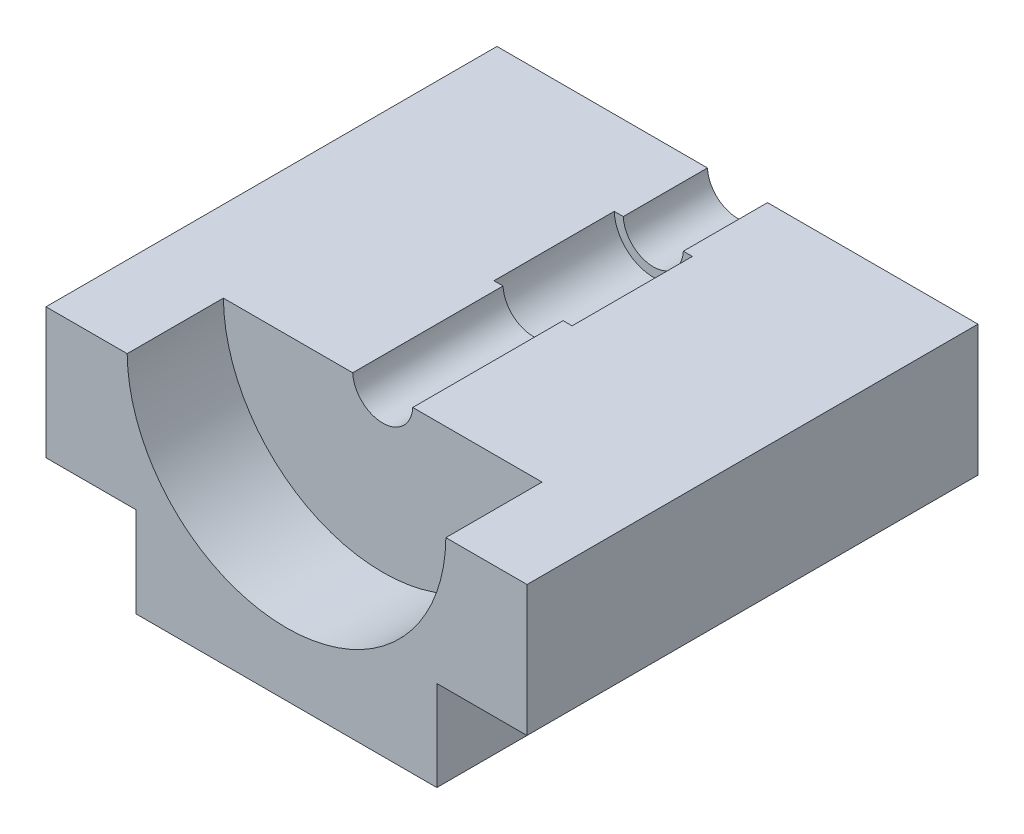
SolidWorks part; units mm, degrees
ref_plane "Front Plane" through (0, 0, 0) normal (0, 0, 1) x (1, 0, 0)
ref_plane "Top Plane" through (0, 0, 0) normal (0, 1, 0) x (1, 0, 0)
ref_plane "Right Plane" through (0, 0, 0) normal (1, 0, 0) x (0, 0, -1)
sketch "Sketch2" plane through (0, 0, 0) normal (0, 0, 1) x (1, 0, 0)
  line L5 (-35, 60) -> (-35, 50)
  line L6 (-52.5, -67.5) -> (52.5, -67.5)
  line L24 (-60, -60) -> (-60, 35)
  line L25 (-27.5, 67.5) -> (27.5, 67.5)
  line L26 (60, -60) -> (60, 35)
  line L27 (0, -100) -> (0, 100) construction
  line L28 (-100, 0) -> (100, 0) construction
  line L29 (-42.5, 42.5) -> (-52.5, 42.5)
  line L34 (35, 60) -> (35, 50)
  line L35 (42.5, 42.5) -> (52.5, 42.5)
  arc A12 (-60, 35) -> (-52.5, 42.5) centre (-52.5, 35) cw
  arc A19 (60, 35) -> (52.5, 42.5) centre (52.5, 35) ccw
  arc A20 (42.5, 42.5) -> (35, 50) centre (42.5, 50) cw
  arc A21 (35, 60) -> (27.5, 67.5) centre (27.5, 60) ccw
  arc A22 (-27.5, 67.5) -> (-35, 60) centre (-27.5, 60) ccw
  arc A23 (-42.5, 42.5) -> (-35, 50) centre (-42.5, 50) ccw
  arc A24 (-60, -60) -> (-52.5, -67.5) centre (-52.5, -60) ccw
  arc A25 (60, -60) -> (52.5, -67.5) centre (52.5, -60) cw
  point P0 (0, 0)
  point P39 (-35, 67.5)
  dimension "D5" = 25
  dimension "D6" = 60
  dimension "D7" = 7.5
  dimension "D2" = 25
  dimension "D3" = 135
  dimension "D8" = 7.5
  dimension "D1" = 67.5
  dimension "D4" = 60
extrude "Boss-Extrude1" add sketch "Sketch2" against normal blind 8
sketch "Sketch3" plane through (0, 0, 0) normal (0, 0, 1) x (1, 0, 0)
  line L0 (0, 100) -> (0, -100) construction
  circle A0 centre (0, -20) radius 13.75
  dimension "D1" = 27.5
  dimension "D2" = 20
extrude "Cut-Extrude1" cut sketch "Sketch3" against normal up to surface (8 mm away) up to face at (0, 21.25, -8)
sketch "Sketch4" plane through (0, 0, -8) normal (0, 0, -1) x (-1, 0, 0)
  line L3 (-40, -57) -> (-40, -20)
  line L4 (0, 100) -> (0, -100) construction
  line L6 (-40, -20) -> (40, -20)
  line L7 (-40, -57) -> (40, -57)
  line L8 (52.5, -67.5) -> (-52.5, -67.5) construction
  line L10 (40, -57) -> (40, -20)
  point P16 (0, -57)
  point P17 (0, -20)
  dimension "D1" = 10.5
  dimension "D3" = 40
  dimension "D4" = 37
extrude "Boss-Extrude2" add sketch "Sketch4" along normal blind 75
sketch "Sketch5" plane through (0, 0, -8) normal (0, 0, -1) x (-1, 0, 0)
  circle A0 centre (0, -20) radius 26.5
  arc A1 (13.75, -20) -> (-13.75, -20) centre (0, -20) ccw construction
  dimension "D1" = 53
extrude "Cut-Extrude2" cut sketch "Sketch5" along normal blind 16
sketch "Sketch6" plane through (0, 0, -8) normal (0, 0, -1) x (-1, 0, 0)
  circle A0 centre (0, -20) radius 6.5
  circle A1 centre (0, -20) radius 13.75 construction
  dimension "D1" = 13
extrude "Cut-Extrude3" cut sketch "Sketch6" along normal up to surface (75 mm away) up to face at (0, -38.5, -83)
sketch "Sketch8" plane through (0, 0, -8) normal (0, 0, -1) x (-1, 0, 0)
  line L1 (-6.5, -20) -> (-5, -20)
  line L2 (5, -20) -> (6.5, -20)
  arc A0 (-5, -20) -> (5, -20) centre (0, -20) ccw
  circle A1 centre (0, -20) radius 13.75 construction
  arc A2 (-6.5, -20) -> (6.5, -20) centre (0, -20) ccw
  arc A3 (-6.5, -20) -> (6.5, -20) centre (0, -20) ccw construction
  dimension "D1" = 10
extrude "Boss-Extrude3" add sketch "Sketch8" along normal blind 25 from surface at 16 starting at face at (0, -28.25, -24)
sketch "Sketch9" plane through (0, 0, -8) normal (0, 0, -1) x (-1, 0, 0)
  line L0 (-6.5, -20) -> (-5, -20)
  line L1 (5, -20) -> (6.5, -20)
  arc A0 (-5, -20) -> (5, -20) centre (0, -20) ccw
  arc A2 (-6.5, -20) -> (6.5, -20) centre (0, -20) ccw
  dimension "D1" = 10
extrude "Boss-Extrude4" add sketch "Sketch9" against normal blind 14 from surface at 75 starting at face at (0, -33.4167, -83)
sketch "Sketch10" plane through (0, 0, 0) normal (0, 0, 1) x (1, 0, 0)
  line L1 (-75, -87.5) -> (75, -87.5)
  line L2 (-75, -87.5) -> (-75, 87.5)
  line L3 (-75, 87.5) -> (75, 87.5)
  line L4 (75, -87.5) -> (75, 87.5)
  line L5 (-75, -87.5) -> (75, 87.5) construction
  line L6 (-75, 87.5) -> (75, -87.5) construction
  point P0 (0, 0)
  dimension "D1" = 150
  dimension "D2" = 175
extrude "Cut-Extrude4" cut sketch "Sketch10" against normal up to surface (8 mm away) up to face at (0, -36.75, -8)
sketch "Sketch12" plane through (0, 0, -8) normal (0, 0, 1) x (1, 0, 0)
  line L0 (-40, -20) -> (-40, -20.25)
  line L1 (-40, -20.25) -> (40, -20.25)
  line L2 (40, -20.25) -> (40, -20)
  line L3 (40, -20) -> (-40, -20)
  line L4 (-40, -57) -> (-40, -20) construction
  line L5 (40, -20) -> (40, -57) construction
  line L6 (5, -20) -> (26.5, -20) construction
  dimension "D1" = 0.25
extrude "Cut-Extrude5" cut sketch "Sketch12" against normal through all both and the other way through all
sketch "Sketch13" plane through (0, 0, -83) normal (0, 0, -1) x (-1, 0, 0)
  line L0 (40, -57) -> (40, -42)
  line L1 (40, -57) -> (40, -20.25) construction
  line L2 (40, -42) -> (25, -42)
  line L3 (25, -42) -> (25, -57)
  line L4 (-40, -57) -> (40, -57) construction
  line L5 (25, -57) -> (40, -57)
  line L6 (0, -115.1141) -> (0, 69.242) construction
  line L7 (-25, -57) -> (-40, -57)
  line L8 (-25, -42) -> (-25, -57)
  line L9 (-40, -42) -> (-25, -42)
  line L10 (-40, -57) -> (-40, -42)
  dimension "D1" = 15
  dimension "D2" = 15
extrude "Cut-Extrude6" cut sketch "Sketch13" against normal up to surface (75 mm away) up to face at (0, -36.875, -8)
